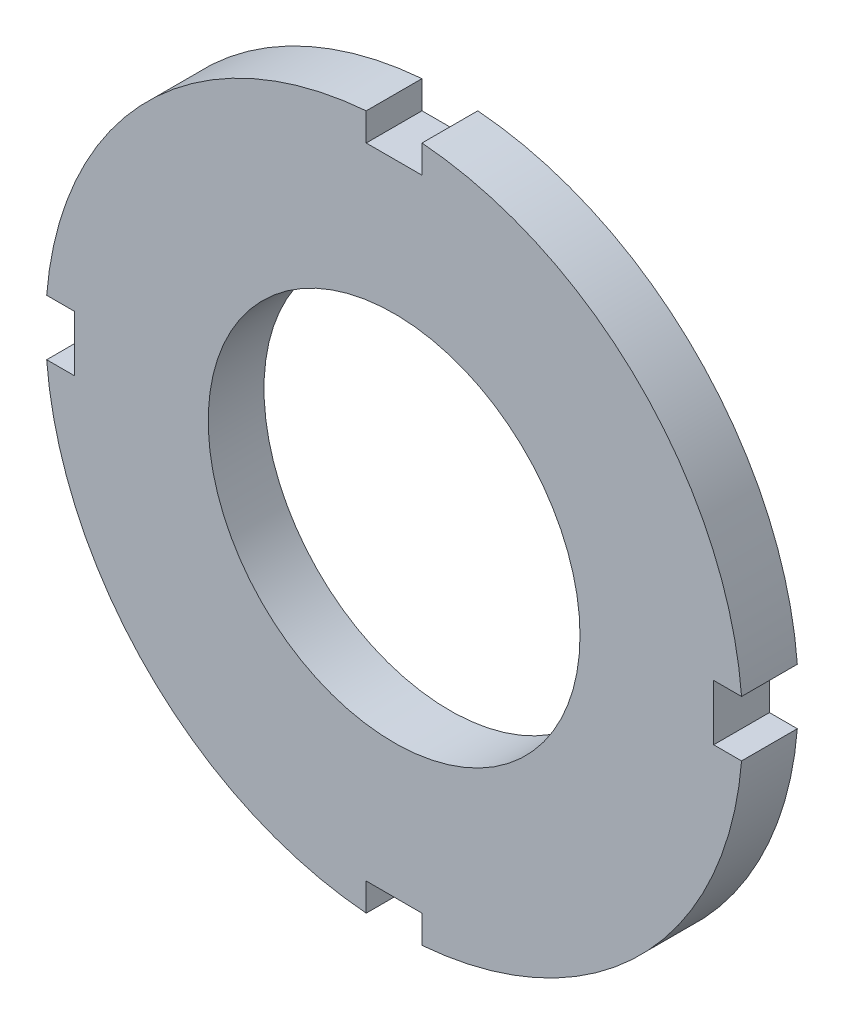
SolidWorks part; units mm, degrees
ref_plane "前视基准面" through (0, 0, 0) normal (0, 0, 1) x (1, 0, 0)
ref_plane "上视基准面" through (0, 0, 0) normal (0, 1, 0) x (1, 0, 0)
ref_plane "右视基准面" through (0, 0, 0) normal (1, 0, 0) x (0, 0, -1)
sketch "草图1" plane through (0, 0, 0) normal (0, 0, 1) x (1, 0, 0)
  line L0 (0, 0) -> (0, 60.1708) construction
  line L1 (34.3798, -3) -> (37.3798, -3)
  line L3 (-3, 34.3798) -> (3, 34.3798)
  line L4 (34.3798, 3) -> (37.3798, 3)
  line L5 (3, 34.3798) -> (3, 37.3798)
  line L6 (34.3798, 3) -> (34.3798, -3)
  line L7 (-3, -34.3798) -> (-3, -37.3798)
  line L8 (-3, 34.3798) -> (-3, 37.3798)
  line L9 (3, -34.3798) -> (3, -37.3798)
  line L10 (3, -34.3798) -> (-3, -34.3798)
  line L11 (-34.3798, 3) -> (-37.3798, 3)
  line L12 (-34.3798, -3) -> (-37.3798, -3)
  line L13 (-34.3798, -3) -> (-34.3798, 3)
  arc A0 (-3, 37.3798) -> (-37.3798, 3) centre (0, 0) ccw
  circle A1 centre (0, 0) radius 20
  arc A2 (37.3798, 3) -> (3, 37.3798) centre (0, 0) ccw
  arc A3 (3, -37.3798) -> (37.3798, -3) centre (0, 0) ccw
  arc A4 (-37.3798, -3) -> (-3, -37.3798) centre (0, 0) ccw
  point P4 (3, 0)
  point P6 (3, 60.1708)
  point P11 (-3, 0)
  point P12 (-3, 60.1708)
  dimension "D1" = 40
  dimension "D2" = 75
extrude "拉伸1" add sketch "草图1" along normal blind 6
